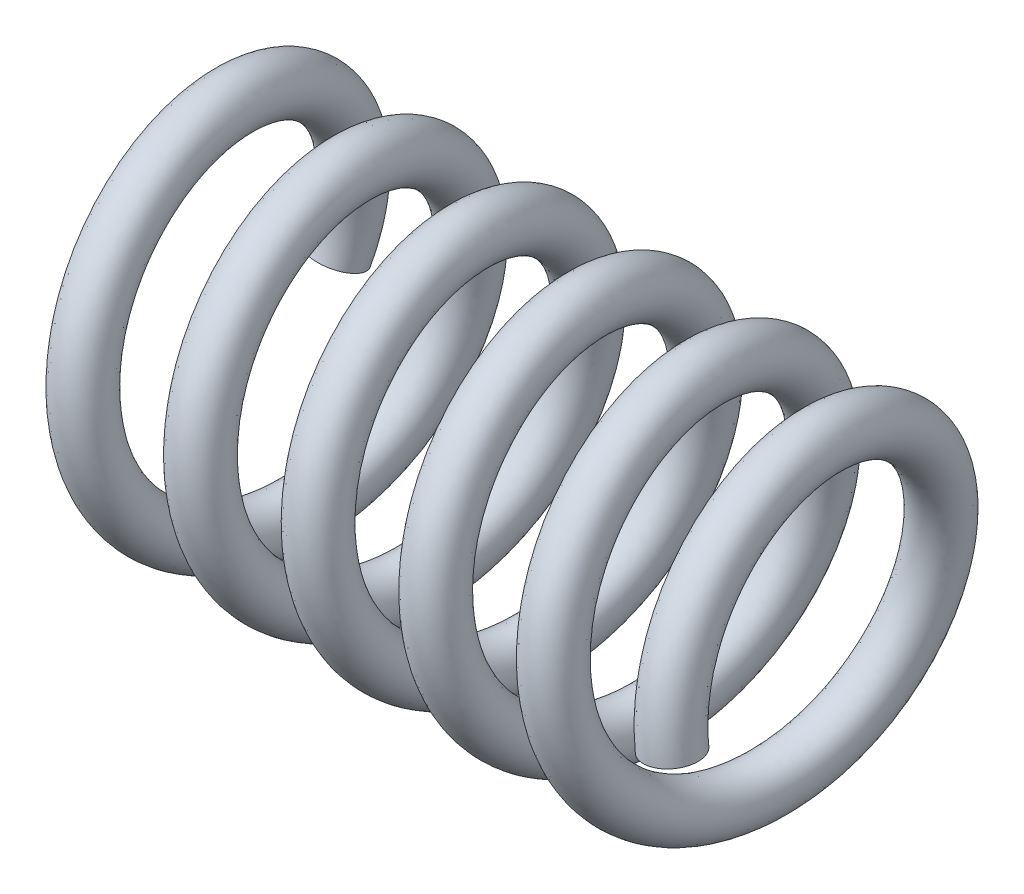
SolidWorks part; units mm, degrees
material "AISI 347 Annealed Stainless Steel (SS)"
ref_plane "Front Plane" through (0, 0, 0) normal (0, 0, 1) x (1, 0, 0)
ref_plane "Top Plane" through (0, 0, 0) normal (0, 1, 0) x (1, 0, 0)
ref_plane "Right Plane" through (0, 0, 0) normal (1, 0, 0) x (0, 0, -1)
sketch "Sketch3" plane through (0, 0, 0) normal (1, 0, 0) x (0, 0, -1)
  circle A0 centre (0, 0) radius 12.5
  dimension "D1" = 25
curve "Helix/Spiral1" pitch 9 height 50 turns 5.5556
sweep "Sweep1" add path "Helix/Spiral1" circular profile diameter 4 parameters "D3"=4
